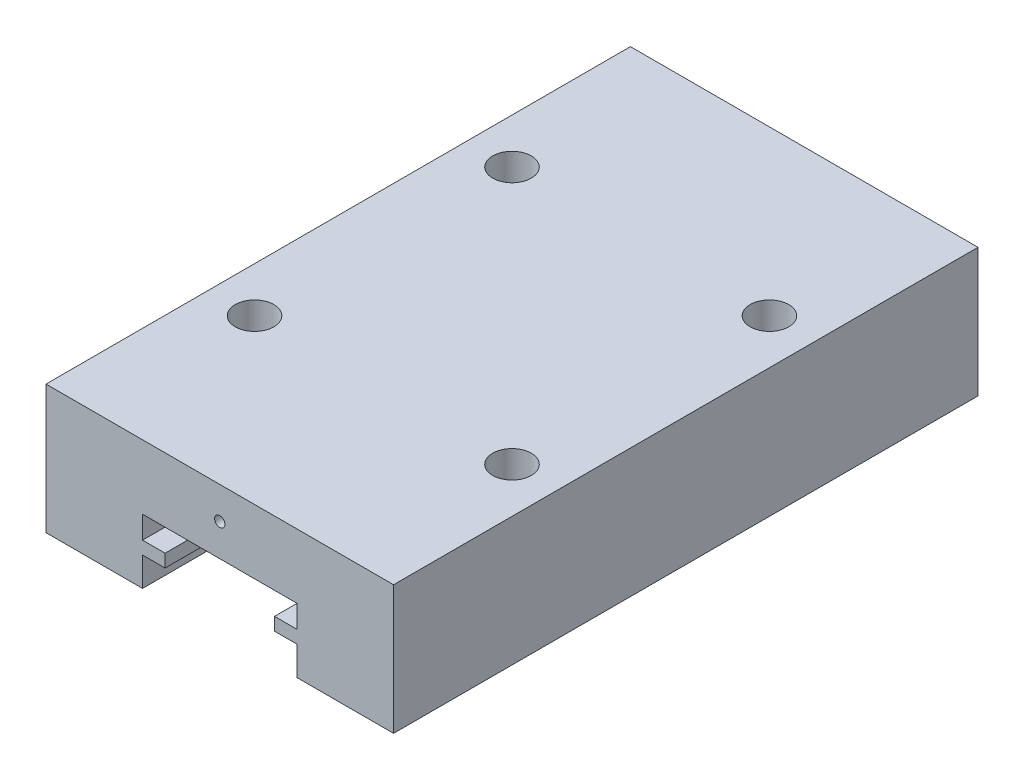
SolidWorks part; units mm, degrees
ref_plane "Płaszczyzna przednia" through (0, 0, 0) normal (0, 0, 1) x (1, 0, 0)
ref_plane "Płaszczyzna górna" through (0, 0, 0) normal (0, 1, 0) x (1, 0, 0)
ref_plane "Płaszczyzna prawa" through (0, 0, 0) normal (1, 0, 0) x (0, 0, -1)
sketch "Szkic1" plane through (0, 0, 0) normal (0, 0, 1) x (1, 0, 0)
  line L0 (7.5, 0) -> (7.5, 2.2479)
  line L1 (0, 0) -> (7.5, 0)
  line L2 (0, 0) -> (0, 10)
  line L3 (0, 10) -> (27, 10)
  line L4 (27, 0) -> (27, 10)
  line L5 (7.5, 2.2479) -> (9.25, 2.2479)
  line L6 (9.25, 2.2479) -> (9.25, 3.2479)
  line L7 (9.25, 3.2479) -> (7.5, 3.2479)
  line L8 (7.5, 3.2479) -> (7.5, 4.9979)
  line L9 (7.5, 4.9979) -> (19.5, 4.9979)
  line L10 (19.5, 4.9979) -> (19.5, 3.2479)
  line L11 (19.5, 3.2479) -> (17.75, 3.2479)
  line L12 (17.75, 3.2479) -> (17.75, 2.2479)
  line L13 (17.75, 2.2479) -> (19.5, 2.2479)
  line L14 (19.5, 2.2479) -> (19.5, 0)
  line L15 (19.5, 0) -> (27, 0)
  dimension "D1" = 27
  dimension "D2" = 10
  dimension "D3" = 7.5
  dimension "D4" = 7.5
  dimension "D5" = 5.0021
  dimension "D6" = 1.75
  dimension "D7" = 1.75
  dimension "D8" = 1
  dimension "D9" = 1.75
  dimension "D10" = 1.75
  dimension "D11" = 1
extrude "Dodanie-wyciągnięcie1" add sketch "Szkic1" along normal blind 45.4
hole_wizard "Otwory ustalające Ø1.0mm1" positions "Szkic3" profile "Szkic4" hole size "Ø1.0" standard "Ansi Metric"
sketch "Szkic3" plane through (0, 0, 45.4) normal (0, 0, 1) x (1, 0, 0)
  line L0 (27, 10) -> (0, 10) construction
  line L1 (27, 0) -> (27, 10) construction
  point P0 (13.5, 7.5)
  dimension "D1" = 2.5
  dimension "D2" = 13.5
sketch "Szkic4" plane through (13.5, 7.5, 45.4) normal (1, 0, 0) x (0, -1, 0)
  line L0 (0, 0) -> (0, 6.7403)
  line L1 (0, 6.7403) -> (0.4, 6.5)
  line L2 (0.4, 6.5) -> (0.4, 0)
  line L5 (0.4, 0) -> (0, 0)
  line L10 (0, 6.7403) -> (-0.4, 6.5) construction
  line L11 (0, -6.35) -> (0, 107.95) construction
  dimension "Œrednica otworu" = 0.8
  dimension "G³êbokoœæ otworu" = 6.5
  dimension "K¹t wiert³a" = 118
hole_wizard "Otwory ustalające Ø1.0mm2" positions "Szkic5" profile "Szkic6" hole size "Ø1.0" standard "Ansi Metric"
sketch "Szkic5" plane through (0, 0, 0) normal (0, 0, -1) x (-1, 0, 0)
  line L0 (-27, 10) -> (0, 10) construction
  line L1 (0, 10) -> (0, 0) construction
  point P0 (-13.5, 7.5)
  dimension "D1" = 2.5
  dimension "D2" = 13.5
sketch "Szkic6" plane through (13.5, 7.5, 0) normal (1, 0, 0) x (0, 1, 0)
  line L0 (0, 0) -> (0, 6.7403)
  line L1 (0, 6.7403) -> (0.4, 6.5)
  line L2 (0.4, 6.5) -> (0.4, 0)
  line L5 (0.4, 0) -> (0, 0)
  line L10 (0, 6.7403) -> (-0.4, 6.5) construction
  line L11 (0, -6.35) -> (0, 107.95) construction
  dimension "Œrednica otworu" = 0.8
  dimension "G³êbokoœæ otworu" = 6.5
  dimension "K¹t wiert³a" = 118
hole_wizard "Ø3.0mm Dowel Hole1" positions "Szkic7" profile "Szkic8" hole size "Ø3.0" standard "ANSI Metric"
sketch "Szkic7" plane through (0, 10, 0) normal (0, 1, 0) x (1, 0, 0)
  line L0 (27, -45.4) -> (0, -45.4) construction
  line L1 (0, -45.4) -> (0, 0) construction
  point P0 (3.5, -32.7)
  point P13 (23.5, -32.7)
  point P14 (23.5, -12.7)
  point P15 (3.5, -12.7)
  dimension "D1" = 12.7
  dimension "D2" = 3.5
  dimension "D3" = 2
  dimension "D4" = 2
sketch "Szkic8" plane through (3.5, 10, 32.7) normal (1, 0, 0) x (0, 0, 1)
  line L0 (0, 0) -> (0, 3.5)
  line L1 (0, 3.5) -> (1.5, 3.5)
  line L2 (1.5, 3.5) -> (1.5, 0)
  line L5 (1.5, 0) -> (0, 0)
  line L10 (0, 3.5) -> (-1.5, 3.5) construction
  line L11 (0, -6.35) -> (0, 107.95) construction
  dimension "Œrednica otworu" = 3
  dimension "G³êbokoœæ otworu" = 3.5
  dimension "K¹t wiert³a" = 180
